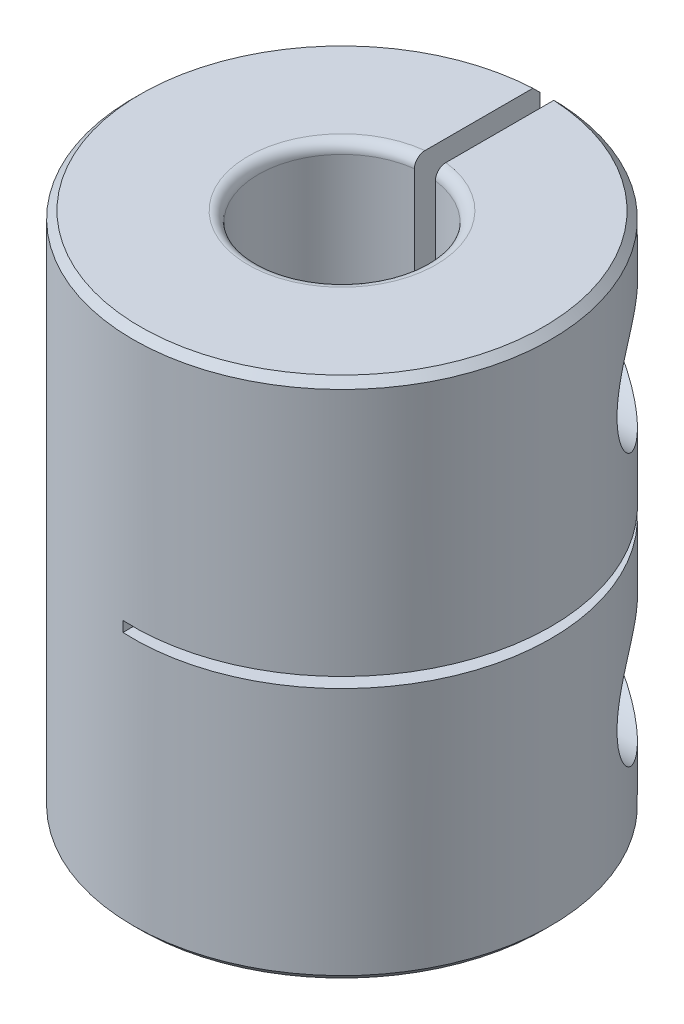
SolidWorks part; units mm, degrees
material "2024-T4"
ref_plane "Front Plane" through (0, 0, 0) normal (0, 0, 1) x (1, 0, 0)
ref_plane "Top Plane" through (0, 0, 0) normal (0, 1, 0) x (1, 0, 0)
ref_plane "Right Plane" through (0, 0, 0) normal (1, 0, 0) x (0, 0, -1)
other "Center of Mass"
sketch "Sketch1" plane through (0, 0, 0) normal (0, 1, 0) x (1, 0, 0)
  circle A0 centre (0, 0) radius 10
  dimension "D1" = 20
extrude "Boss-Extrude1" add sketch "Sketch1" along normal blind 25
sketch "Sketch2" plane through (0, 25, 0) normal (0, 1, 0) x (1, 0, 0)
  circle A0 centre (0, 0) radius 4
  dimension "D1" = 8
extrude "Cut-Extrude1" cut sketch "Sketch2" against normal blind 12.5
sketch "Sketch3" plane through (0, 0, 0) normal (0, -1, 0) x (1, 0, 0)
  circle A0 centre (0, 0) radius 2.5
  dimension "D1" = 5
extrude "Cut-Extrude2" cut sketch "Sketch3" against normal blind 12.5
fillet "Fillet1" radius 0.5 2 edges at (0, 0, -2.5) (0, 25, 4)
chamfer "Chamfer2" distance 0.5 angle 45 1 edges at (0, 12.5, -2.5)
chamfer "Chamfer3" distance 0.35 angle 45 2 edges at (0, 0, 10) (0, 25, 10)
ref_plane "Plane1" through (10, 0, 0) normal (-1, 0, 0) x (0, 0, 1)
ref_plane "Plane2" through (-10, 0, 0) normal (1, 0, 0) x (0, 0, -1)
ref_plane "Plane3" through (0, 0, 10) normal (0, 0, -1) x (-1, 0, 0)
ref_plane "Plane4" through (0, 0, -10) normal (0, 0, 1) x (1, 0, 0)
sketch "Sketch4" plane through (10, 0, 0) normal (-1, 0, 0) x (0, 0, 1)
  line L1 (4, -25) -> (-4, -25) construction
  line L2 (4, -25) -> (4, 25) construction
  line L3 (4, 25) -> (-4, 25) construction
  line L4 (-4, -25) -> (-4, 25) construction
  line L5 (4, -25) -> (-4, 25) construction
  line L6 (4, 25) -> (-4, -25) construction
  line L8 (-4, 19) -> (-10, 19) construction
  line L9 (-10, -11) -> (-10, 11) construction
  line L10 (0, 25) -> (0, 0) construction
  line L11 (4.5, 25) -> (-4.5, 25) construction
  line L12 (0, 12.5) -> (-10, 12.5) construction
  circle A0 centre (-7, 19) radius 3
  circle A1 centre (-7, 6) radius 3
  point P0 (0, 0)
  dimension "D4" = 6
  dimension "D1" = 50
  dimension "D2" = 8
  dimension "D3" = 6
extrude "Cut-Extrude3" cut sketch "Sketch4" along normal blind 8
sketch "Sketch5" plane through (2, 0, 0) normal (1, 0, 0) x (0, 0, -1)
  circle A1 centre (7, 19) radius 1.25
  circle A2 centre (7, 6) radius 1.25
  dimension "D1" = 2.5
  dimension "D2" = 2.5
extrude "Cut-Extrude4" cut sketch "Sketch5" against normal through all
sketch "Sketch6" plane through (0, 0, -10) normal (0, 0, 1) x (1, 0, 0)
  line L0 (0, 0) -> (0, 25) construction
  line L1 (4.5, 25) -> (-4.5, 25) construction
  line L2 (0.5, 0) -> (0.5, 25)
  line L3 (-0.5, 0) -> (-0.5, 25)
  line L4 (0.5, 25) -> (-0.5, 25)
  line L5 (0.5, 0) -> (-0.5, 0)
  dimension "D1" = 0.5
  dimension "D2" = 0.5
extrude "Cut-Extrude5" cut sketch "Sketch6" along normal blind 13.95
sketch "Sketch7" plane through (10, 0, 0) normal (-1, 0, 0) x (0, 0, 1)
  line L0 (10.0065, 12.5) -> (-10, 12.5) construction
  line L1 (-10, -11) -> (-10, 11) construction
  line L3 (9.65, 25) -> (-9.637, 25) construction
  line L4 (0.0065, 25) -> (0, 0) construction
  line L5 (10.0065, 12.75) -> (-10, 12.75)
  line L6 (10.0065, 12.25) -> (-10, 12.25)
  line L7 (-10, 12.75) -> (-10, 12.25)
  line L10 (10.0065, 12.25) -> (10.0065, 12.75)
  point P2 (0.0032, 12.5)
  dimension "D1" = 0.25
  dimension "D2" = 0.25
extrude "Cut-Extrude6" cut sketch "Sketch7" along normal up to surface (10.5 mm away) up to face at (-0.5, 6.397, 3.2584)
sketch "Sketch8" plane through (0, 12.25, 0) normal (0, 1, 0) x (1, 0, 0)
  arc A1 (-0.5, 3.9686) -> (0.5, 3.9686) centre (0, 0) ccw construction
  circle A2 centre (0, 0) radius 4
extrude "Cut-Extrude7" cut sketch "Sketch8" along normal blind 13.975
